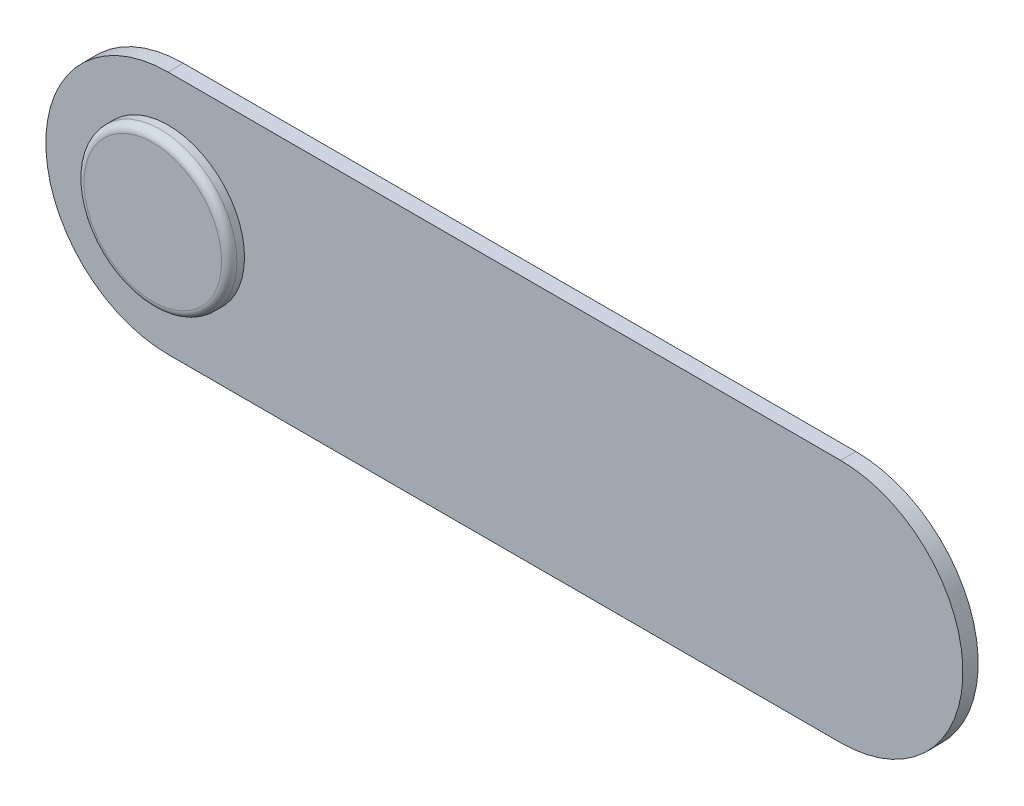
SolidWorks part; units mm, degrees
ref_plane "前视基准面" through (0, 0, 0) normal (0, 0, 1) x (1, 0, 0)
ref_plane "上视基准面" through (0, 0, 0) normal (0, 1, 0) x (1, 0, 0)
ref_plane "右视基准面" through (0, 0, 0) normal (1, 0, 0) x (0, 0, -1)
sketch "草图1" plane through (0, 0, 0) normal (0, 0, 1) x (1, 0, 0)
  line L0 (0, 0) -> (22, 0) construction
  line L1 (0, 4) -> (22, 4)
  line L2 (0, -4) -> (22, -4)
  arc A0 (0, 4) -> (0, -4) centre (0, 0) ccw
  arc A1 (22, -4) -> (22, 4) centre (22, 0) ccw
  point P3 (11, 0)
  dimension "D1" = 8
  dimension "D2" = 22
extrude "凸台-拉伸1" add sketch "草图1" along normal blind 0.5
sketch "草图2" plane through (0, 0, 0.5) normal (0, 0, 1) x (1, 0, 0)
  circle A0 centre (0, 0) radius 2.5
  dimension "D1" = 5
extrude "凸台-拉伸2" add sketch "草图2" along normal blind 0.5
fillet "圆角1" radius 0.25 1 edges at (2.5, 0, 1)
